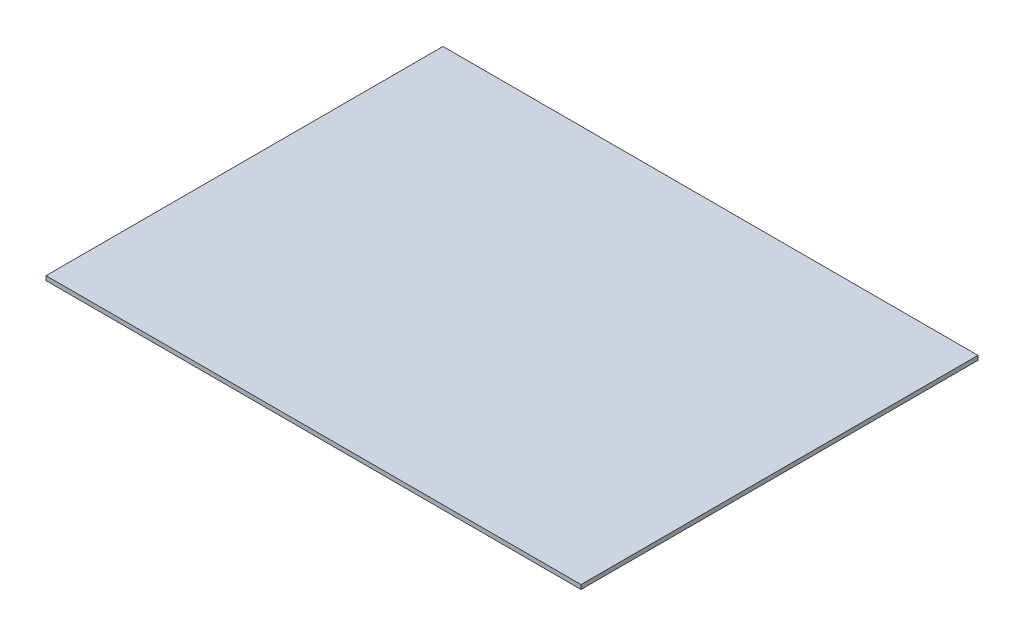
SolidWorks part; units mm, degrees
ref_plane "Front Plane" through (0, 0, 0) normal (0, 0, 1) x (1, 0, 0)
ref_plane "Top Plane" through (0, 0, 0) normal (0, 1, 0) x (1, 0, 0)
ref_plane "Right Plane" through (0, 0, 0) normal (1, 0, 0) x (0, 0, -1)
sketch "Sketch1" plane through (0, 0, 0) normal (0, 1, 0) x (1, 0, 0)
  line L1 (0, 0) -> (393.7, 0)
  line L2 (0, 0) -> (0, 292.1)
  line L3 (0, 292.1) -> (393.7, 292.1)
  line L4 (393.7, 0) -> (393.7, 292.1)
  dimension "D1" = 393.7
  dimension "D2" = 292.1
extrude "Boss-Extrude1" add sketch "Sketch1" along normal blind 3.175
